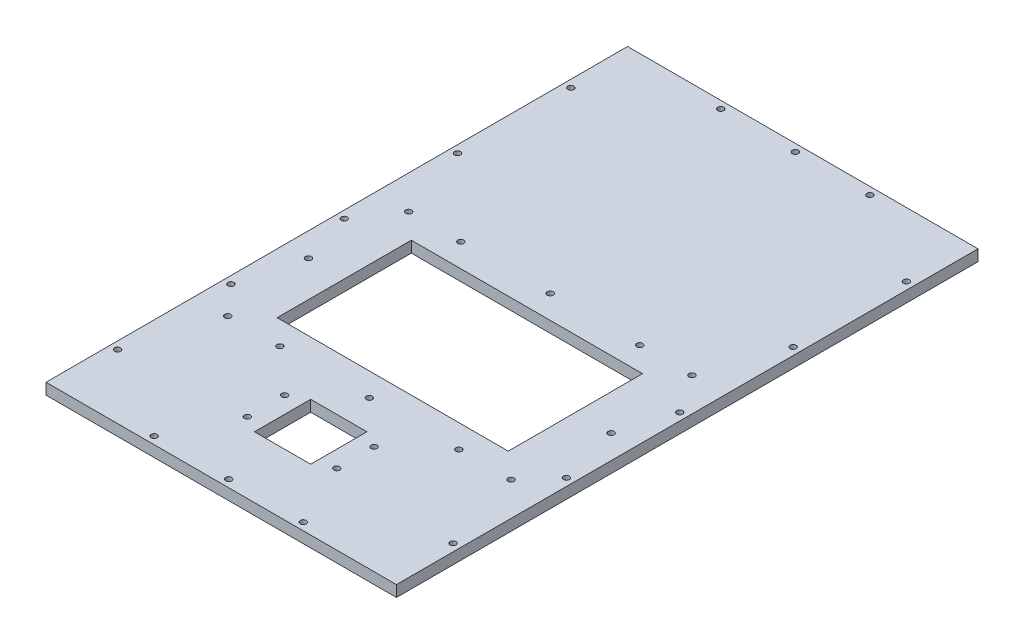
SolidWorks part; units mm, degrees
material "Acrylic (Medium-high impact)"
ref_plane "Front Plane" through (0, 0, 0) normal (0, 0, 1) x (1, 0, 0)
ref_plane "Top Plane" through (0, 0, 0) normal (0, 1, 0) x (1, 0, 0)
ref_plane "Right Plane" through (0, 0, 0) normal (1, 0, 0) x (0, 0, -1)
sketch "Sketch1" plane through (0, 0, 0) normal (0, 1, 0) x (1, 0, 0)
  line L1 (-149.225, -247.65) -> (149.225, -247.65)
  line L2 (-149.225, -247.65) -> (-149.225, 247.65)
  line L3 (-149.225, 247.65) -> (149.225, 247.65)
  line L4 (149.225, -247.65) -> (149.225, 247.65)
  line L5 (-149.225, -247.65) -> (149.225, 247.65) construction
  line L6 (-149.225, 247.65) -> (149.225, -247.65) construction
  line L7 (73.025, -247.65) -> (-130.175, -247.65)
  line L11 (-384.175, -247.65) -> (-231.775, -247.65)
  point P0 (0, 0)
  dimension "D1" = 298.45
  dimension "D2" = 495.3
extrude "Boss-Extrude1" add sketch "Sketch1" along normal mid plane 9.525 contours L1 L4 L3 L2
sketch "Sketch2" [suppressed] plane through (0, 0, 0) normal (0, 1, 0) x (1, 0, 0)
  line L0 (-250.825, -28.575) -> (250.825, -28.575) construction
  line L1 (161.925, -28.575) -> (60.325, -28.575)
  line L2 (161.925, -28.575) -> (161.925, -92.075)
  line L3 (161.925, -92.075) -> (60.325, -92.075)
  line L4 (60.325, -28.575) -> (60.325, -92.075)
  line L5 (0, -5.2388) -> (0, 5.2388) construction
  line L6 (-79.375, -28.575) -> (-168.275, -28.575)
  line L7 (-79.375, -28.575) -> (-79.375, -92.075)
  line L8 (-79.375, -92.075) -> (-168.275, -92.075)
  line L9 (-168.275, -28.575) -> (-168.275, -92.075)
  line L10 (250.825, -28.575) -> (250.825, 28.575) construction
  line L11 (-250.825, -28.575) -> (-250.825, 28.575) construction
  line L12 (-250.825, 28.575) -> (250.825, 28.575) construction
  line L13 (250.825, -28.575) -> (250.825, 28.575) construction
  line L14 (161.925, -28.575) -> (250.825, -28.575)
  line L15 (161.925, -28.575) -> (161.925, -71.755)
  line L16 (161.925, -71.755) -> (250.825, -71.755)
  line L17 (250.825, -28.575) -> (250.825, -71.755)
  line L18 (-250.825, -28.575) -> (-250.825, 28.575) construction
  line L19 (-79.375, -28.575) -> (60.325, -28.575)
  line L20 (-79.375, -28.575) -> (-79.375, -53.975)
  line L21 (-79.375, -53.975) -> (60.325, -53.975)
  line L22 (60.325, -28.575) -> (60.325, -53.975)
  line L23 (-168.275, -28.575) -> (-250.825, -28.575)
  line L24 (-168.275, -28.575) -> (-168.275, -71.755)
  line L25 (-168.275, -71.755) -> (-250.825, -71.755)
  line L26 (-250.825, -28.575) -> (-250.825, -71.755)
  point P19 (60.325, -92.075)
  dimension "D1" = 139.7
  dimension "D2" = 88.9
  dimension "D3" = 82.55
  dimension "D4" = 79.375
  dimension "D5" = 120.65
  dimension "D6" = 43.18
  dimension "D7" = 25.4
  dimension "D8" = 43.18
extrude "Boss-Extrude2" [suppressed] add sketch "Sketch2" along normal mid plane 9.525 contours L6 L9 L8 L7 | L23 L26 L25 L9 | L7 L21 L4 L19 | L17 L14 L2 L16
sketch "Sketch3" plane through (0, 4.7625, 0) normal (0, 1, 0) x (1, 0, 0)
  line L0 (-149.225, 247.65) -> (149.225, 247.65) construction
  line L1 (-98.425, 12.7) -> (98.425, 12.7)
  line L2 (-98.425, 12.7) -> (-98.425, -101.6)
  line L3 (-98.425, -101.6) -> (98.425, -101.6)
  line L4 (98.425, 12.7) -> (98.425, -101.6)
  line L5 (-98.425, 12.7) -> (98.425, -101.6) construction
  line L6 (-98.425, -101.6) -> (98.425, 12.7) construction
  line L7 (-149.225, -247.65) -> (149.225, -247.65) construction
  point P0 (0, -44.45)
  point P7 (0, 247.65)
  point P8 (0, 12.7)
  dimension "D1" = 196.85
  dimension "D2" = 114.3
  dimension "D3" = 203.2
extrude "Cut-Extrude1" cut sketch "Sketch3" against normal through all and the other way through all
sketch "Sketch4" [suppressed] plane through (0, -4.7625, 0) normal (0, -1, 0) x (1, 0, 0)
  line L0 (-107.315, 31.75) -> (107.315, 31.75) construction
  line L1 (-107.315, 33.9979) -> (107.315, 33.9979)
  line L2 (-107.315, 29.5021) -> (107.315, 29.5021)
  line L3 (-107.315, 6.35) -> (107.315, 6.35) construction
  line L4 (-107.315, 8.5979) -> (107.315, 8.5979)
  line L5 (-107.315, 4.1021) -> (107.315, 4.1021)
  arc A0 (-107.315, 33.9979) -> (-107.315, 29.5021) centre (-107.315, 31.75) ccw
  arc A1 (107.315, 29.5021) -> (107.315, 33.9979) centre (107.315, 31.75) ccw
  arc A2 (-107.315, 8.5979) -> (-107.315, 4.1021) centre (-107.315, 6.35) ccw
  arc A3 (107.315, 4.1021) -> (107.315, 8.5979) centre (107.315, 6.35) ccw
  point P0 (-107.315, 31.75)
  point P1 (107.315, 31.75)
  point P3 (107.315, 6.35)
  point P5 (-107.315, 6.35)
  point P10 (0, 31.75)
  point P15 (0, 6.35)
  dimension "D1" = 4.4958
  dimension "D2" = 4.4958
extrude "Cut-Extrude2" [suppressed] cut sketch "Sketch4" against normal through all
sketch "Sketch5" [suppressed] plane through (0, -4.7625, 0) normal (0, -1, 0) x (1, 0, 0)
  line L0 (69.85, 79.375) -> (69.85, -9.525) construction
  line L1 (60.325, 53.975) -> (60.325, 92.075) construction
  line L2 (161.925, 92.075) -> (60.325, 92.075) construction
  line L3 (-247.65, -22.225) -> (247.65, -22.225) construction
  line L4 (69.85, 79.375) -> (69.85, -9.525) construction
  line L5 (72.0979, 79.375) -> (72.0979, -9.525)
  line L6 (67.6021, 79.375) -> (67.6021, -9.525)
  line L7 (-88.9, 79.375) -> (-88.9, -9.525) construction
  line L8 (-79.375, 53.975) -> (-79.375, 92.075) construction
  line L9 (-79.375, 92.075) -> (-168.275, 92.075) construction
  line L10 (-88.9, 79.375) -> (-88.9, -9.525) construction
  line L11 (-86.6521, 79.375) -> (-86.6521, -9.525)
  line L12 (-91.1479, 79.375) -> (-91.1479, -9.525)
  arc A0 (72.0979, 79.375) -> (67.6021, 79.375) centre (69.85, 79.375) ccw
  arc A1 (67.6021, -9.525) -> (72.0979, -9.525) centre (69.85, -9.525) ccw
  arc A2 (-86.6521, 79.375) -> (-91.1479, 79.375) centre (-88.9, 79.375) ccw
  arc A3 (-91.1479, -9.525) -> (-86.6521, -9.525) centre (-88.9, -9.525) ccw
  point P8 (69.85, 34.925)
  point P19 (-88.9, 34.925)
  dimension "D1" = 9.525
  dimension "D2" = 12.7
  dimension "D3" = 12.7
  dimension "D4" = 4.4958
  dimension "D5" = 9.525
  dimension "D6" = 12.7
  dimension "D7" = 12.7
  dimension "D8" = 4.4958
extrude "Cut-Extrude3" [suppressed] cut sketch "Sketch5" against normal through all contours L12 A3 L11 A2 | L6 A1 L5 A0
sketch "Sketch6" [suppressed] plane through (0, 4.7625, 0) normal (0, 1, 0) x (1, 0, 0)
  line L0 (-79.375, -38.1) -> (-79.375, 38.1) construction
  line L1 (-88.9, -50.8) -> (-88.9, 50.8) construction
  line L2 (-88.9, -50.8) -> (88.9, -50.8) construction
  line L3 (-88.9, 50.8) -> (88.9, 50.8) construction
  line L4 (79.375, -38.1) -> (79.375, 38.1) construction
  line L5 (88.9, -50.8) -> (88.9, 50.8) construction
  line L6 (-79.375, -38.1) -> (-79.375, 38.1) construction
  line L7 (-81.6229, -38.1) -> (-81.6229, 38.1)
  line L8 (-77.1271, -38.1) -> (-77.1271, 38.1)
  line L9 (79.375, -38.1) -> (79.375, 38.1) construction
  line L10 (77.1271, -38.1) -> (77.1271, 38.1)
  line L11 (81.6229, -38.1) -> (81.6229, 38.1)
  arc A0 (-81.6229, -38.1) -> (-77.1271, -38.1) centre (-79.375, -38.1) ccw
  arc A1 (-77.1271, 38.1) -> (-81.6229, 38.1) centre (-79.375, 38.1) ccw
  arc A2 (77.1271, -38.1) -> (81.6229, -38.1) centre (79.375, -38.1) ccw
  arc A3 (81.6229, 38.1) -> (77.1271, 38.1) centre (79.375, 38.1) ccw
  point P12 (-79.375, 0)
  point P17 (79.375, 0)
  dimension "D1" = 9.525
  dimension "D2" = 12.7
  dimension "D3" = 12.7
  dimension "D4" = 9.525
  dimension "D5" = 12.7
  dimension "D6" = 12.7
  dimension "D7" = 4.4958
  dimension "D8" = 4.4958
extrude "Cut-Extrude4" [suppressed] cut sketch "Sketch6" against normal through all
sketch "Sketch7" [suppressed] plane through (0, 4.7625, 0) normal (0, 1, 0) x (1, 0, 0)
  point P0 (115.1313, 66.802)
  point P1 (139.827, 42.1063)
  point P3 (-139.827, 42.1063)
  point P5 (-115.1313, 66.802)
hole_wizard "#12 Clearance Hole1" [suppressed] positions "Sketch8" profile "Sketch9" hole size "#12" standard "ANSI Inch"
sketch "Sketch8" plane through (0, 4.7625, 0) normal (0, 1, 0) x (1, 0, 0)
  point P0 (-139.827, 42.1063)
  point P3 (-115.1313, 66.802)
  point P6 (115.1313, 66.802)
  point P9 (139.827, 42.1063)
sketch "Sketch9" plane through (-139.827, 4.7625, -42.1063) normal (1, 0, 0) x (0, 0, 1)
  line L0 (0, 0) -> (0, 18.1964)
  line L1 (0, 18.1964) -> (2.8067, 16.51)
  line L2 (2.8067, 16.51) -> (2.8067, 0)
  line L5 (2.8067, 0) -> (0, 0)
  line L10 (0, 18.1964) -> (-2.8067, 16.51) construction
  line L11 (0, -6.35) -> (0, 107.95) construction
  dimension "Hole Dia." = 5.6134
  dimension "Hole Depth" = 16.51
  dimension "Drill Angle" = 118
sketch "Sketch10" [suppressed] plane through (0, -4.7625, 0) normal (0, -1, 0) x (1, 0, 0)
  point P0 (223.8375, -6.35)
  point P1 (223.8375, 19.05)
  point P3 (-223.8375, 19.05)
  point P5 (-223.8375, -6.35)
hole_wizard "#12 Clearance Hole3" [suppressed] positions "Sketch11" profile "Sketch12" hole size "#12" standard "ANSI Inch"
sketch "Sketch11" plane through (0, -4.7625, 0) normal (0, -1, 0) x (-1, 0, 0)
  point P0 (-223.8375, -19.05)
  point P3 (-223.8375, 6.35)
  point P6 (223.8375, -19.05)
  point P9 (223.8375, 6.35)
sketch "Sketch12" plane through (223.8375, -4.7625, 19.05) normal (1, 0, 0) x (0, 0, -1)
  line L0 (0, 0) -> (0, 18.1964)
  line L1 (0, 18.1964) -> (2.8067, 16.51)
  line L2 (2.8067, 16.51) -> (2.8067, 0)
  line L5 (2.8067, 0) -> (0, 0)
  line L10 (0, 18.1964) -> (-2.8067, 16.51) construction
  line L11 (0, -6.35) -> (0, 107.95) construction
  dimension "Hole Dia." = 5.6134
  dimension "Hole Depth" = 16.51
  dimension "Drill Angle" = 118
sketch "Sketch13" [suppressed] plane through (0, -4.7625, 0) normal (0, -1, 0) x (1, 0, 0)
  point P0 (133.35, -223.8375)
  point P1 (107.95, -223.8375)
  point P3 (-107.95, -223.8375)
  point P5 (-133.35, -223.8375)
  point P7 (133.35, 223.8375)
  point P9 (107.95, 223.8375)
  point P11 (-107.95, 223.8375)
  point P13 (-133.35, 223.8375)
hole_wizard "#12 Clearance Hole2" [suppressed] positions "Sketch14" profile "Sketch15" hole size "#12" standard "ANSI Inch"
sketch "Sketch14" [suppressed] plane through (0, -4.7625, 0) normal (0, -1, 0) x (-1, 0, 0)
  point P0 (107.95, -223.8375)
  point P3 (133.35, -223.8375)
  point P6 (133.35, 223.8375)
  point P9 (107.95, 223.8375)
  point P12 (-133.35, 223.8375)
  point P15 (-107.95, 223.8375)
  point P18 (-133.35, -223.8375)
  point P21 (-107.95, -223.8375)
sketch "Sketch15" plane through (-107.95, -4.7625, 223.8375) normal (1, 0, 0) x (0, 0, -1)
  line L0 (0, 0) -> (0, 18.1964)
  line L1 (0, 18.1964) -> (2.8067, 16.51)
  line L2 (2.8067, 16.51) -> (2.8067, 0)
  line L5 (2.8067, 0) -> (0, 0)
  line L10 (0, 18.1964) -> (-2.8067, 16.51) construction
  line L11 (0, -6.35) -> (0, 107.95) construction
  dimension "Hole Dia." = 5.6134
  dimension "Hole Depth" = 16.51
  dimension "Drill Angle" = 118
sketch "Sketch16" [suppressed] plane through (0, 4.7625, 0) normal (0, 1, 0) x (1, 0, 0)
  line L0 (88.9, -50.8) -> (88.9, 50.8) construction
  line L1 (-88.9, -50.8) -> (-88.9, 50.8) construction
  line L2 (-88.9, -50.8) -> (88.9, -50.8) construction
  point P0 (79.375, -38.1)
  point P1 (-79.375, -38.1)
  dimension "D1" = 9.525
  dimension "D2" = 9.525
  dimension "D3" = 12.7
hole_wizard "#8 Clearance Hole1" [suppressed] positions "Sketch17" profile "Sketch19" hole size "#8" standard "ANSI Inch"
sketch "Sketch17" plane through (0, 4.7625, 0) normal (0, 1, 0) x (1, 0, 0)
  point P0 (79.375, -38.1)
  point P3 (-79.375, -38.1)
sketch "Sketch19" plane through (79.375, 4.7625, 38.1) normal (1, 0, 0) x (0, 0, 1)
  line L0 (0, 0) -> (0, 12.0187)
  line L1 (0, 12.0187) -> (2.2479, 10.668)
  line L2 (2.2479, 10.668) -> (2.2479, 0)
  line L5 (2.2479, 0) -> (0, 0)
  line L10 (0, 12.0187) -> (-2.2479, 10.668) construction
  line L11 (0, -6.35) -> (0, 107.95) construction
  dimension "Hole Dia." = 4.4958
  dimension "Hole Depth" = 10.668
  dimension "Drill Angle" = 118
sketch "Sketch20" plane through (0, -4.7625, 0) normal (0, -1, 0) x (1, 0, 0)
  line L0 (-149.225, 247.65) -> (149.225, 247.65) construction
  line L1 (23.9395, 147.5105) -> (-23.9395, 147.5105)
  line L2 (23.9395, 147.5105) -> (23.9395, 195.3895)
  line L3 (23.9395, 195.3895) -> (-23.9395, 195.3895)
  line L4 (-23.9395, 147.5105) -> (-23.9395, 195.3895)
  line L5 (23.9395, 147.5105) -> (-23.9395, 195.3895) construction
  line L6 (23.9395, 195.3895) -> (-23.9395, 147.5105) construction
  line L8 (38.1, 155.575) -> (-38.1, 155.575) construction
  line L9 (38.1, 155.575) -> (38.1, 187.325) construction
  line L10 (38.1, 187.325) -> (-38.1, 187.325) construction
  line L11 (-38.1, 155.575) -> (-38.1, 187.325) construction
  point P0 (0, 171.45)
  point P7 (0, 247.65)
  point P8 (38.1, 155.575)
  point P9 (38.1, 187.325)
  point P10 (-38.1, 155.575)
  point P11 (-38.1, 187.325)
  point P18 (0, 187.325)
  point P19 (0, 195.3895)
  point P20 (-38.1, 171.45)
  point P21 (-23.9395, 171.45)
  dimension "D1" = 47.879
  dimension "D2" = 47.879
  dimension "D3" = 38.1
  dimension "D4" = 15.875
  dimension "D5" = 76.2
extrude "Cut-Extrude5" cut sketch "Sketch20" against normal through all contours L1 L4 L3 L2
hole_wizard "#10 Clearance Hole1" positions "Sketch21" profile "Sketch22" hole size "#10" standard "ANSI Inch"
sketch "Sketch21" plane through (0, -4.7625, 0) normal (0, -1, 0) x (-1, 0, 0)
  point P0 (-38.1, -155.575)
  point P3 (38.1, -155.575)
  point P6 (38.1, -187.325)
  point P9 (-38.1, -187.325)
sketch "Sketch22" plane through (38.1, -4.7625, 155.575) normal (1, 0, 0) x (0, 0, -1)
  line L0 (0, 0) -> (0, 12.2018)
  line L1 (0, 12.2018) -> (2.5527, 10.668)
  line L2 (2.5527, 10.668) -> (2.5527, 0)
  line L5 (2.5527, 0) -> (0, 0)
  line L10 (0, 12.2018) -> (-2.5527, 10.668) construction
  line L11 (0, -6.35) -> (0, 107.95) construction
  dimension "Hole Dia." = 5.1054
  dimension "Hole Depth" = 10.668
  dimension "Drill Angle" = 118
sketch "Sketch23" [suppressed] plane through (-250.825, 0, 0) normal (-1, 0, 0) x (0, 0, 1)
  line L4 (-28.575, -4.7625) -> (71.755, -4.7625)
  line L5 (71.755, -4.7625) -> (71.755, 4.7625)
  line L6 (71.755, 4.7625) -> (-28.575, 4.7625)
  line L7 (-28.575, 4.7625) -> (-28.575, -4.7625)
  line L8 (-28.575, -4.7625) -> (71.755, -4.7625)
  line L9 (71.755, -4.7625) -> (71.755, 4.7625)
  line L10 (71.755, 4.7625) -> (-28.575, 4.7625)
  line L11 (-28.575, 4.7625) -> (-28.575, -4.7625)
  dimension "D1" = 0
extrude "Boss-Extrude3" [suppressed] add sketch "Sketch23" along normal blind 6.35
mirror "Mirror1" [suppressed] about plane through (0, 0, 0) normal (1, 0, 0)
sketch "Sketch27" [suppressed] plane through (0, 4.7625, 0) normal (0, 1, 0) x (1, 0, 0)
  line L1 (257.175, -71.755) -> (257.175, 28.575) construction
  line L2 (-257.175, 28.575) -> (257.175, 28.575) construction
  point P0 (241.3, 12.7)
  dimension "D1" = 15.875
  dimension "D2" = 15.875
hole_wizard "#10 Clearance Hole2" [suppressed] positions "Sketch28" profile "Sketch30" hole size "#10" standard "ANSI Inch"
sketch "Sketch28" plane through (0, 4.7625, 0) normal (0, 1, 0) x (1, 0, 0)
  point P0 (241.3, 12.7)
sketch "Sketch30" plane through (241.3, 4.7625, -12.7) normal (1, 0, 0) x (0, 0, 1)
  line L0 (0, 0) -> (0, 9.525)
  line L1 (0, 9.525) -> (2.5527, 9.525)
  line L2 (2.5527, 9.525) -> (2.5527, 0)
  line L5 (2.5527, 0) -> (0, 0)
  line L11 (0, -6.35) -> (0, 107.95) construction
  dimension "Thru Hole Dia." = 5.1054
  dimension "Thru Hole Depth" = 9.525
pattern_linear "LPattern1" [suppressed] count 6 spacing 96.52
sketch "Sketch31" [suppressed] plane through (0, 4.7625, 0) normal (0, 1, 0) x (1, 0, 0)
  line L1 (0, -5.2388) -> (0, 5.2388) construction
  line L2 (-149.225, 76.2) -> (149.225, 76.2) construction
  point P0 (-95.25, 60.325)
  dimension "D1" = 15.875
  dimension "D2" = 95.25
hole_wizard "#10 Clearance Hole3" [suppressed] positions "Sketch32" profile "Sketch33" hole size "#10" standard "ANSI Inch"
sketch "Sketch32" plane through (0, 4.7625, 0) normal (0, 1, 0) x (1, 0, 0)
  point P0 (-95.25, 60.325)
sketch "Sketch33" plane through (-95.25, 4.7625, -60.325) normal (1, 0, 0) x (0, 0, 1)
  line L0 (0, 0) -> (0, 9.525)
  line L1 (0, 9.525) -> (2.5527, 9.525)
  line L2 (2.5527, 9.525) -> (2.5527, 0)
  line L5 (2.5527, 0) -> (0, 0)
  line L11 (0, -6.35) -> (0, 107.95) construction
  dimension "Thru Hole Dia." = 5.1054
  dimension "Thru Hole Depth" = 9.525
pattern_linear "LPattern2" [suppressed] count 4 spacing 63.5
sketch "Sketch34" plane through (0, 4.7625, 0) normal (0, 1, 0) x (1, 0, 0)
  line L0 (0, -5.2388) -> (0, 5.2388) construction
  line L1 (-149.225, 247.65) -> (149.225, 247.65) construction
  point P0 (-63.5, 241.3)
  dimension "D1" = 63.5
  dimension "D2" = 6.35
hole_wizard "#10 Clearance Hole4" positions "Sketch35" profile "Sketch36" hole size "#10" standard "ANSI Inch" end condition up to next
sketch "Sketch35" plane through (0, 4.7625, 0) normal (0, 1, 0) x (1, 0, 0)
  point P0 (-63.5, 241.3)
sketch "Sketch36" plane through (-63.5, 4.7625, -241.3) normal (1, 0, 0) x (0, 0, 1)
  line L0 (0, 0) -> (0, 9.525)
  line L1 (0, 9.525) -> (2.5527, 9.525)
  line L2 (2.5527, 9.525) -> (2.5527, 0)
  line L5 (2.5527, 0) -> (0, 0)
  line L11 (0, -6.35) -> (0, 107.95) construction
  dimension "Thru Hole Dia." = 5.1054
  dimension "Thru Hole Depth" = 9.525
pattern_linear "LPattern3" count 3 spacing 63.5 along (1, 0, 0) of "#10 Clearance Hole4"
mirror "Mirror2" about plane through (0, 0, 0) normal (0, 0, 1) of "LPattern3", "#10 Clearance Hole4"
sketch "Sketch37" plane through (0, 4.7625, 0) normal (0, 1, 0) x (1, 0, 0)
  line L0 (-5.2388, 0) -> (5.2388, 0) construction
  line L1 (-149.225, -247.65) -> (-149.225, 247.65) construction
  point P0 (-142.875, 0)
  dimension "D1" = 6.35
hole_wizard "#10 Clearance Hole5" positions "Sketch38" profile "Sketch39" hole size "#10" standard "ANSI Inch" end condition up to next
sketch "Sketch38" plane through (0, 4.7625, 0) normal (0, 1, 0) x (1, 0, 0)
  point P0 (-142.875, 0)
sketch "Sketch39" plane through (-142.875, 4.7625, 0) normal (1, 0, 0) x (0, 0, 1)
  line L0 (0, 0) -> (0, 9.525)
  line L1 (0, 9.525) -> (2.5527, 9.525)
  line L2 (2.5527, 9.525) -> (2.5527, 0)
  line L5 (2.5527, 0) -> (0, 0)
  line L11 (0, -6.35) -> (0, 107.95) construction
  dimension "Thru Hole Dia." = 5.1054
  dimension "Thru Hole Depth" = 9.525
pattern_linear "LPattern4" count 3 spacing 96.52 along (0, 0, -1) count 3 spacing 96.52 along (0, 0, 1) of "#10 Clearance Hole5"
mirror "Mirror3" about plane through (0, 0, 0) normal (1, 0, 0) of "LPattern4", "#10 Clearance Hole5"
sketch "Sketch40" [suppressed] plane through (0, 4.7625, 0) normal (0, 1, 0) x (1, 0, 0)
  line L0 (-79.375, -53.975) -> (-79.375, -92.075) construction
  line L3 (-88.9, -79.375) -> (-88.9, -9.525) construction
  line L4 (-91.1479, -79.375) -> (-91.1479, -9.525)
  line L5 (-86.6521, -79.375) -> (-86.6521, -9.525)
  line L6 (69.85, -79.375) -> (69.85, -9.525) construction
  line L7 (67.6021, -79.375) -> (67.6021, -9.525)
  line L8 (72.0979, -79.375) -> (72.0979, -9.525)
  line L9 (60.325, -53.975) -> (60.325, -92.075) construction
  line L12 (-79.375, -92.075) -> (-168.275, -92.075) construction
  line L13 (161.925, -92.075) -> (60.325, -92.075) construction
  arc A2 (-91.1479, -79.375) -> (-86.6521, -79.375) centre (-88.9, -79.375) ccw
  arc A3 (-86.6521, -9.525) -> (-91.1479, -9.525) centre (-88.9, -9.525) ccw
  arc A4 (67.6021, -79.375) -> (72.0979, -79.375) centre (69.85, -79.375) ccw
  arc A5 (72.0979, -9.525) -> (67.6021, -9.525) centre (69.85, -9.525) ccw
  point P7 (-88.9, -44.45)
  point P14 (69.85, -44.45)
  dimension "D1" = 9.525
  dimension "D2" = 4.4958
  dimension "D3" = 4.4958
  dimension "D4" = 9.525
  dimension "D5" = 12.7
  dimension "D6" = 12.7
  dimension "D7" = 69.85
  dimension "D8" = 69.85
extrude "Cut-Extrude6" [suppressed] cut sketch "Sketch40" against normal up to next
sketch "Sketch41" plane through (0, -4.7625, 0) normal (0, -1, 0) x (1, 0, 0)
  point P0 (120.65, -32.5755)
  point P1 (-120.65, -32.5755)
  point P3 (-120.65, 121.4755)
  point P5 (120.65, 121.4755)
hole_wizard "#10 Clearance Hole6" positions "Sketch42" profile "Sketch43" hole size "#10" standard "ANSI Inch" end condition through all
sketch "Sketch42" plane through (0, 4.7625, 0) normal (0, 1, 0) x (1, 0, 0)
  point P0 (120.65, 32.5755)
  point P3 (120.65, -121.4755)
  point P6 (-120.65, -121.4755)
  point P9 (-120.65, 32.5755)
sketch "Sketch43" plane through (120.65, 4.7625, -32.5755) normal (1, 0, 0) x (0, 0, 1)
  line L0 (0, 0) -> (0, 9.525)
  line L1 (0, 9.525) -> (2.5527, 9.525)
  line L2 (2.5527, 9.525) -> (2.5527, 0)
  line L5 (2.5527, 0) -> (0, 0)
  line L11 (0, -6.35) -> (0, 107.95) construction
  dimension "Thru Hole Dia." = 5.1054
  dimension "Thru Hole Depth" = 9.525
sketch "Sketch44" plane through (0, 4.7625, 0) normal (0, 1, 0) x (1, 0, 0)
  line L0 (0, -5.2388) -> (0, 5.2388) construction
  line L2 (120.65, 32.5755) -> (-120.65, 32.5755) construction
  line L3 (120.65, -121.4755) -> (-120.65, -121.4755) construction
  point P0 (76.2, 32.5755)
  point P1 (0, 32.5755)
  point P2 (-76.2, 32.5755)
  point P3 (76.2, -121.4755)
  point P4 (0, -121.4755)
  point P5 (-76.2, -121.4755)
  dimension "D1" = 76.2
  dimension "D2" = 76.2
hole_wizard "#10 Clearance Hole7" positions "Sketch45" profile "Sketch46" hole size "#10" standard "ANSI Inch" end condition through all
sketch "Sketch45" plane through (0, 4.7625, 0) normal (0, 1, 0) x (1, 0, 0)
  point P0 (76.2, 32.5755)
  point P3 (0, 32.5755)
  point P6 (-76.2, 32.5755)
  point P9 (76.2, -121.4755)
  point P12 (0, -121.4755)
  point P15 (-76.2, -121.4755)
sketch "Sketch46" plane through (76.2, 4.7625, -32.5755) normal (1, 0, 0) x (0, 0, 1)
  line L0 (0, 0) -> (0, 9.525)
  line L1 (0, 9.525) -> (2.5527, 9.525)
  line L2 (2.5527, 9.525) -> (2.5527, 0)
  line L5 (2.5527, 0) -> (0, 0)
  line L11 (0, -6.35) -> (0, 107.95) construction
  dimension "Thru Hole Dia." = 5.1054
  dimension "Thru Hole Depth" = 9.525
sketch "Sketch47" [suppressed] plane through (0, 4.7625, 0) normal (0, 1, 0) x (1, 0, 0)
  line L1 (-142.875, 0) -> (-142.875, -96.52) construction
  line L2 (142.875, 0) -> (142.875, -96.52) construction
  point P0 (-142.875, -71.12)
  point P1 (142.875, -25.4)
  point P2 (-142.875, -25.4)
  point P3 (142.875, -71.12)
  dimension "D1" = 25.4
  dimension "D2" = 25.4
  dimension "D3" = 25.4
  dimension "D4" = 25.4
hole_wizard "#10 Clearance Hole8" [suppressed] positions "Sketch48" profile "Sketch49" hole size "#10" standard "ANSI Inch"
sketch "Sketch48" [suppressed] plane through (0, 4.7625, 0) normal (0, 1, 0) x (1, 0, 0)
  point P0 (-142.875, -71.12)
  point P3 (142.875, -25.4)
  point P7 (-142.875, -25.4)
  point P10 (142.875, -71.12)
sketch "Sketch49" plane through (-142.875, 4.7625, 71.12) normal (1, 0, 0) x (0, 0, 1)
  line L0 (0, 0) -> (0, 9.525)
  line L1 (0, 9.525) -> (2.5527, 9.525)
  line L2 (2.5527, 9.525) -> (2.5527, 0)
  line L5 (2.5527, 0) -> (0, 0)
  line L11 (0, -6.35) -> (0, 107.95) construction
  dimension "Thru Hole Dia." = 5.1054
  dimension "Thru Hole Depth" = 9.525
sketch "Sketch50" [suppressed] plane through (0, 0, 0) normal (0, 1, 0) x (1, 0, 0)
  line L1 (-209.55, -50.8) -> (209.55, -50.8)
  line L2 (-209.55, -50.8) -> (-209.55, 50.8)
  line L3 (-209.55, 50.8) -> (209.55, 50.8)
  line L4 (209.55, -50.8) -> (209.55, 50.8)
  line L5 (-209.55, -50.8) -> (209.55, 50.8) construction
  line L6 (-209.55, 50.8) -> (209.55, -50.8) construction
  point P0 (0, 0)
  dimension "D1" = 419.1
  dimension "D2" = 101.6
extrude "Boss-Extrude4" [suppressed] add sketch "Sketch50" along normal blind 9.525
sketch "Sketch51" [suppressed] plane through (0, 0, 0) normal (0, -1, 0) x (1, 0, 0)
  line L0 (144.78, -12.7) -> (144.78, -50.8) construction
  line L1 (152.7175, -12.7) -> (152.7175, -50.8)
  line L2 (136.8425, -12.7) -> (136.8425, -50.8)
  line L3 (209.55, -50.8) -> (-209.55, -50.8) construction
  line L4 (209.55, 50.8) -> (209.55, -50.8) construction
  line L5 (48.26, -50.8) -> (48.26, -12.7) construction
  line L7 (40.3225, -50.8) -> (40.3225, -12.7)
  line L8 (56.1975, -50.8) -> (56.1975, -12.7)
  arc A0 (152.7175, -12.7) -> (136.8425, -12.7) centre (144.78, -12.7) ccw
  arc A1 (136.8425, -50.8) -> (152.7175, -50.8) centre (144.78, -50.8) ccw
  arc A2 (40.3225, -50.8) -> (56.1975, -50.8) centre (48.26, -50.8) ccw
  arc A3 (56.1975, -12.7) -> (40.3225, -12.7) centre (48.26, -12.7) ccw
  point P2 (144.78, -31.75)
  point P7 (48.26, -31.75)
  dimension "D1" = 38.1
  dimension "D2" = 64.77
  dimension "D3" = 15.875
  dimension "D4" = 15.875
  dimension "D5" = 96.52
extrude "Cut-Extrude7" [suppressed] cut sketch "Sketch51" against normal up to next
mirror "Mirror4" [suppressed] about plane through (0, 0, 0) normal (1, 0, 0)
sketch "Sketch52" [suppressed] plane through (0, 4.7625, 0) normal (0, 1, 0) x (1, 0, 0)
  line L0 (-79.375, -92.075) -> (-168.275, -92.075) construction
  line L1 (161.925, -92.075) -> (60.325, -92.075) construction
  point P0 (-123.825, -38.1)
  point P1 (111.125, -38.1)
  point P4 (-123.825, -92.075)
  point P7 (111.125, -92.075)
  dimension "D1" = 53.975
hole_wizard "#10 Clearance Hole9" [suppressed] positions "Sketch53" profile "Sketch54" hole size "#10" standard "ANSI Inch"
sketch "Sketch53" plane through (0, 4.7625, 0) normal (0, 1, 0) x (1, 0, 0)
  point P0 (-123.825, -38.1)
  point P3 (111.125, -38.1)
sketch "Sketch54" plane through (-123.825, 4.7625, 38.1) normal (1, 0, 0) x (0, 0, 1)
  line L0 (0, 0) -> (0, 9.525)
  line L1 (0, 9.525) -> (2.5527, 9.525)
  line L2 (2.5527, 9.525) -> (2.5527, 0)
  line L5 (2.5527, 0) -> (0, 0)
  line L11 (0, -6.35) -> (0, 107.95) construction
  dimension "Thru Hole Dia." = 5.1054
  dimension "Thru Hole Depth" = 9.525
sketch "Sketch55" [suppressed] plane through (0, 0, 0) normal (0, -1, 0) x (1, 0, 0)
  line L0 (111.125, 34.925) -> (111.125, -34.925) construction
  line L1 (113.792, 34.925) -> (113.792, -34.925)
  line L2 (108.458, 34.925) -> (108.458, -34.925)
  line L3 (-123.825, 34.925) -> (-123.825, -34.925) construction
  line L4 (209.55, 50.8) -> (209.55, -50.8) construction
  line L5 (-121.158, 34.925) -> (-121.158, -34.925)
  line L6 (-126.492, 34.925) -> (-126.492, -34.925)
  line L7 (-209.55, -50.8) -> (-209.55, 50.8) construction
  arc A0 (113.792, 34.925) -> (108.458, 34.925) centre (111.125, 34.925) ccw
  arc A1 (108.458, -34.925) -> (113.792, -34.925) centre (111.125, -34.925) ccw
  arc A2 (-121.158, 34.925) -> (-126.492, 34.925) centre (-123.825, 34.925) ccw
  arc A3 (-126.492, -34.925) -> (-121.158, -34.925) centre (-123.825, -34.925) ccw
  point P2 (111.125, 0)
  point P11 (209.55, 0)
  point P12 (-123.825, 0)
  dimension "D1" = 5.334
  dimension "D2" = 69.85
  dimension "D3" = 98.425
  dimension "D4" = 85.725
  dimension "D5" = 5.334
  dimension "D6" = 69.85
extrude "Cut-Extrude8" [suppressed] cut sketch "Sketch55" against normal up to next contours L6 A3 L5 A2 | L2 A1 L1 A0
sketch "Sketch56" [suppressed] plane through (0, 4.7625, 0) normal (0, 1, 0) x (1, 0, 0)
  line L0 (-257.175, -71.755) -> (-257.175, 28.575) construction
  line L1 (-168.275, -71.755) -> (-257.175, -71.755) construction
  line L2 (257.175, -71.755) -> (257.175, 28.575) construction
  line L3 (161.925, -71.755) -> (257.175, -71.755) construction
  point P0 (-234.95, -62.23)
  point P5 (234.95, -62.23)
  dimension "D1" = 22.225
  dimension "D2" = 9.525
  dimension "D3" = 22.225
  dimension "D4" = 9.525
hole_wizard "#10-32 Tapped Hole2" [suppressed] positions "Sketch57" profile "Sketch58" tap size "#10-32" standard "ANSI Inch"
sketch "Sketch57" plane through (0, 4.7625, 0) normal (0, 1, 0) x (1, 0, 0)
  point P0 (234.95, -62.23)
  point P3 (-234.95, -62.23)
sketch "Sketch58" plane through (234.95, 4.7625, 62.23) normal (1, 0, 0) x (0, 0, 1)
  line L0 (0, 0) -> (0, 9.525)
  line L1 (0, 9.525) -> (2.0193, 9.525)
  line L2 (2.0193, 9.525) -> (2.0193, 0)
  line L5 (2.0193, 0) -> (0, 0)
  line L11 (0, -6.35) -> (0, 107.95) construction
  dimension "Thru Tap Drill Dia." = 4.0386
  dimension "Thru Tap Drill Depth" = 9.525
sketch "Sketch59" [suppressed] plane through (0, 4.7625, 0) normal (0, 1, 0) x (1, 0, 0)
  line L0 (-149.225, -76.2) -> (149.225, -76.2) construction
  line L1 (149.225, -76.2) -> (149.225, 76.2) construction
  line L2 (-149.225, -76.2) -> (-149.225, 76.2) construction
  point P0 (139.7, -14.605)
  point P1 (-139.7, -14.605)
  dimension "D1" = 61.595
  dimension "D2" = 9.525
  dimension "D3" = 9.525
hole_wizard "#10-32 Tapped Hole1" [suppressed] positions "Sketch60" profile "Sketch62" tap size "#10-32" standard "ANSI Inch"
sketch "Sketch60" plane through (0, 4.7625, 0) normal (0, 1, 0) x (1, 0, 0)
  point P0 (-139.7, -14.605)
  point P3 (139.7, -14.605)
sketch "Sketch62" plane through (-139.7, 4.7625, 14.605) normal (1, 0, 0) x (0, 0, 1)
  line L0 (0, 0) -> (0, 9.525)
  line L1 (0, 9.525) -> (2.0193, 9.525)
  line L2 (2.0193, 9.525) -> (2.0193, 0)
  line L5 (2.0193, 0) -> (0, 0)
  line L11 (0, -6.35) -> (0, 107.95) construction
  dimension "Thru Tap Drill Dia." = 4.0386
  dimension "Thru Tap Drill Depth" = 9.525
cosmetic thread "Hole Thread1" [suppressed] parameters "D2"=4.826
cosmetic thread "Hole Thread2" [suppressed] parameters "D2"=4.826
sketch "Sketch63" [suppressed] plane through (0, 4.7625, 0) normal (0, 1, 0) x (1, 0, 0)
  line L0 (-149.225, 76.2) -> (149.225, 76.2) construction
  line L1 (-149.225, -76.2) -> (-149.225, 76.2) construction
  point P0 (-65.0875, 19.05)
  point P1 (-26.9875, 19.05)
  dimension "D1" = 38.1
  dimension "D2" = 57.15
  dimension "D3" = 84.1375
hole_wizard "1/4 Clearance Hole1" [suppressed] positions "Sketch64" profile "Sketch65" hole size "1/4" standard "ANSI Inch"
sketch "Sketch64" plane through (0, 4.7625, 0) normal (0, 1, 0) x (1, 0, 0)
  point P0 (-65.0875, 19.05)
  point P3 (-26.9875, 19.05)
sketch "Sketch65" plane through (-65.0875, 4.7625, -19.05) normal (1, 0, 0) x (0, 0, 1)
  line L0 (0, 0) -> (0, 9.525)
  line L1 (0, 9.525) -> (3.3782, 9.525)
  line L2 (3.3782, 9.525) -> (3.3782, 0)
  line L5 (3.3782, 0) -> (0, 0)
  line L11 (0, -6.35) -> (0, 107.95) construction
  dimension "Thru Hole Dia." = 6.7564
  dimension "Thru Hole Depth" = 9.525
mirror "Mirror5" [suppressed] about plane through (0, 0, 0) normal (1, 0, 0)
sketch "Sketch66" plane through (0, 4.7625, 0) normal (0, 1, 0) x (1, 0, 0)
  line L0 (-128.905, -44.45) -> (128.905, -44.45) construction
  line L1 (98.425, -101.6) -> (98.425, 12.7) construction
  line L2 (149.225, -247.65) -> (149.225, 247.65) construction
  line L3 (0, -5.2388) -> (0, 5.2388) construction
  point P4 (98.425, -44.45)
  point P7 (0, -44.45)
  dimension "D1" = 20.32
hole_wizard "1/4-20 Tapped Hole1" positions "Sketch67" profile "Sketch68" tap size "1/4-20" standard "ANSI Inch" end condition through all
sketch "Sketch67" plane through (0, 4.7625, 0) normal (0, 1, 0) x (1, 0, 0)
  point P0 (-128.905, -44.45)
  point P3 (128.905, -44.45)
sketch "Sketch68" plane through (-128.905, 4.7625, 44.45) normal (1, 0, 0) x (0, 0, 1)
  line L0 (0, 0) -> (0, 9.525)
  line L1 (0, 9.525) -> (2.5527, 9.525)
  line L2 (2.5527, 9.525) -> (2.5527, 0)
  line L5 (2.5527, 0) -> (0, 0)
  line L11 (0, -6.35) -> (0, 107.95) construction
  dimension "Thru Tap Drill Dia." = 5.1054
  dimension "Thru Tap Drill Depth" = 9.525
